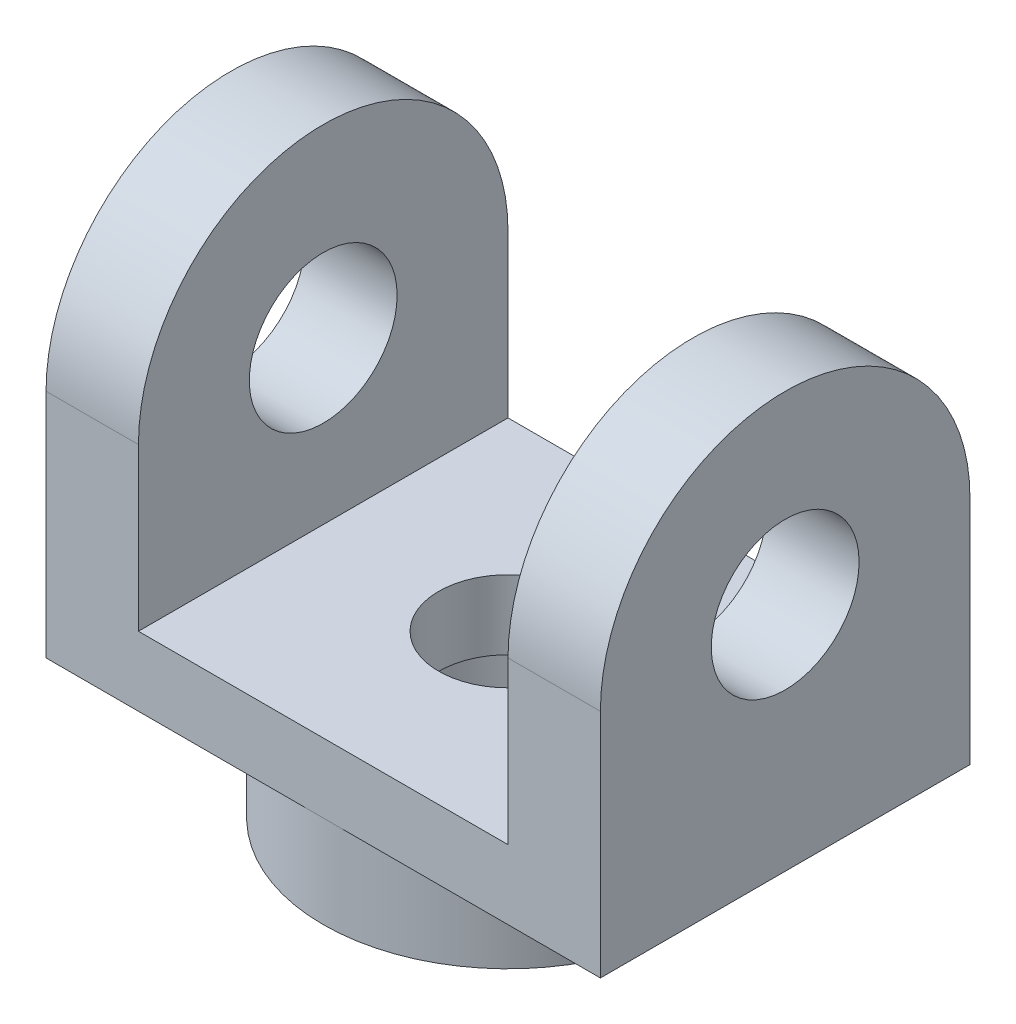
SolidWorks part; units mm, degrees
ref_plane "Front Plane" through (0, 0, 0) normal (0, 0, 1) x (1, 0, 0)
ref_plane "Top Plane" through (0, 0, 0) normal (0, 1, 0) x (1, 0, 0)
ref_plane "Right Plane" through (0, 0, 0) normal (1, 0, 0) x (0, 0, -1)
sketch "Sketch1" plane through (0, 0, 0) normal (0, 1, 0) x (1, 0, 0)
  line L0 (-98.6963, 0) -> (131.5116, 0) construction
  line L1 (0, 81.0362) -> (0, -75.5252) construction
  circle A0 centre (0, 0) radius 15
  circle A1 centre (0, 0) radius 30
  circle A2 centre (0, 0) radius 40
  dimension "D1" = 80
  dimension "D2" = 60
  dimension "D3" = 30
extrude "Boss-Extrude2" add sketch "Sketch1" along normal blind 20 contours A2 A1
sketch "Sketch2" plane through (0, 20, 0) normal (0, 1, 0) x (1, 0, 0)
  line L0 (-59.7746, 0) -> (100.1567, 0) construction
  line L1 (0, 80.8783) -> (0, -72.665) construction
  line L3 (-60, -40) -> (60, -40)
  line L4 (-60, -40) -> (-60, 40)
  line L5 (-60, 40) -> (60, 40)
  line L6 (60, -40) -> (60, 40)
  line L7 (-60, -40) -> (60, 40) construction
  line L8 (-60, 40) -> (60, -40) construction
  point P5 (0, 0)
  dimension "D1" = 80
  dimension "D2" = 120
extrude "Boss-Extrude3" add sketch "Sketch2" along normal blind 15
sketch "Sketch3" plane through (0, 20, 0) normal (0, -1, 0) x (1, 0, 0)
  circle A0 centre (0, 0) radius 15
  dimension "D1" = 30
extrude "Cut-Extrude1" cut sketch "Sketch3" against normal blind 37
sketch "Sketch7" plane through (0, 0, 40) normal (0, 0, 1) x (1, 0, 0)
  line L0 (0, -17.6342) -> (0, 55.1848) construction
  line L1 (60.4486, 0) -> (-65.8049, 0) construction
  line L3 (60, 35) -> (40, 35)
  line L4 (60, 35) -> (60, 70)
  line L5 (60, 70) -> (40, 70)
  line L6 (40, 35) -> (40, 70)
  dimension "D1" = 20
  dimension "D2" = 35
extrude "Boss-Extrude5" add sketch "Sketch7" against normal blind 80
sketch "Sketch8" plane through (40, 0, 0) normal (-1, 0, 0) x (0, 0, 1)
  line L0 (0, -21.9941) -> (0, 111.5577) construction
  line L1 (97.0197, 0) -> (-83.8442, 0) construction
  line L2 (-40, 70) -> (40, 70) construction
  line L7 (40, 35) -> (40, 70)
  line L8 (40, 70) -> (-40, 70)
  line L9 (-40, 70) -> (-40, 35)
  line L10 (-40, 35) -> (40, 35)
  line L12 (40, 70) -> (-40, 70)
  arc A0 (40, 70) -> (-40, 70) centre (0, 70) ccw
  point P8 (0, 110)
  dimension "D1" = 40
  dimension "D2" = 0
extrude "Boss-Extrude6" add sketch "Sketch8" against normal blind 20
sketch "Sketch9" plane through (60, 0, 0) normal (1, 0, 0) x (0, 0, -1)
  line L0 (0, -17.8705) -> (0, 141.8129) construction
  line L1 (120.9063, 70) -> (-96.9429, 70) construction
  line L2 (-40, 20) -> (40, 20) construction
  circle A0 centre (0, 70) radius 16
  dimension "D2" = 32
  dimension "D1" = 50
extrude "Cut-Extrude2" cut sketch "Sketch9" against normal blind 20
sketch "Sketch10" plane through (0, 0, -40) normal (0, 0, -1) x (-1, 0, 0)
  line L0 (0, -20.7026) -> (0, 135.2774) construction
mirror "Mirror1" about plane through (0, 0, 0) normal (1, 0, 0) of "Cut-Extrude2", "Boss-Extrude6", "Boss-Extrude5"
